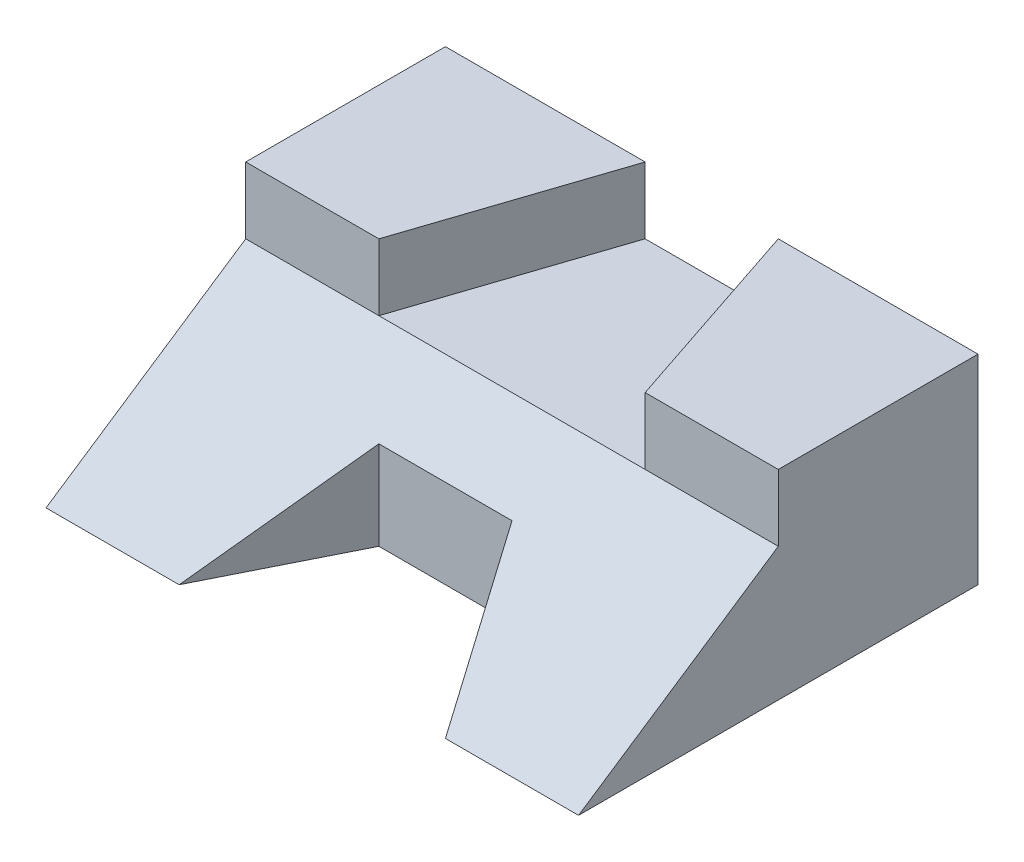
SolidWorks part; units mm, degrees
material "1.0570 (S355J2G3)"
ref_plane "Front Plane" through (0, 0, 0) normal (0, 0, 1) x (1, 0, 0)
ref_plane "Top Plane" through (0, 0, 0) normal (0, 1, 0) x (1, 0, 0)
ref_plane "Right Plane" through (0, 0, 0) normal (1, 0, 0) x (0, 0, -1)
sketch "Sketch2" plane through (0, 0, 0) normal (1, 0, 0) x (0, 0, -1)
  line L0 (0, 0) -> (0, 30)
  line L1 (0, 30) -> (-30, 30)
  line L2 (-30, 30) -> (-30, 20)
  line L3 (-30, 20) -> (-60, 0)
  line L4 (-60, 0) -> (0, 0)
  dimension "D1" = 10
  dimension "D2" = 30
  dimension "D3" = 30
  dimension "D4" = 60
extrude "Boss-Extrude1" add sketch "Sketch2" along normal blind 80
sketch "Sketch3" plane through (0, 30, 0) normal (0, 1, 0) x (1, 0, 0)
  line L0 (40, 0) -> (40, -48.9031) construction
  line L7 (80, 0) -> (0, 0) construction
  line L8 (50, 0) -> (30, 0)
  line L9 (30, 0) -> (20, -30)
  line L10 (80, -30) -> (0, -30) construction
  line L11 (20, -30) -> (60, -30)
  line L12 (40, -30) -> (40, 0)
  line L13 (50, 0) -> (60, -30)
  dimension "D1" = 20
  dimension "D2" = 40
extrude "Cut-Extrude1" cut sketch "Sketch3" against normal blind 10 contours L11 L13 L8 L9
sketch "Sketch4" plane through (0, 0, 0) normal (0, -1, 0) x (1, 0, 0)
  line L0 (40, 0) -> (40, 68.0688) construction
  line L1 (80, 0) -> (0, 0) construction
  line L2 (60, 60) -> (20, 60)
  line L3 (80, 60) -> (0, 60) construction
  line L4 (20, 60) -> (30, 40)
  line L5 (30, 40) -> (50, 40)
  line L6 (40, 40) -> (40, 60)
  line L7 (60, 60) -> (50, 40)
  dimension "D1" = 20
  dimension "D2" = 20
  dimension "D3" = 40
extrude "Cut-Extrude2" cut sketch "Sketch4" against normal up to next contours L5 L7 L2 L4
